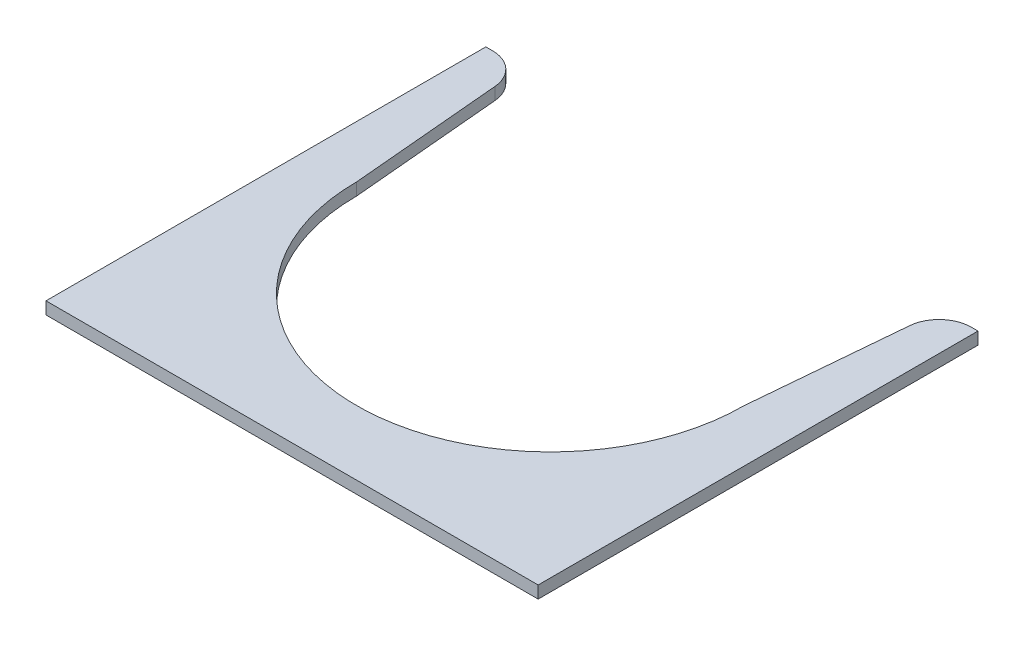
SolidWorks part; units mm, degrees
ref_plane "Front Plane" through (0, 0, 0) normal (0, 0, 1) x (1, 0, 0)
ref_plane "Top Plane" through (0, 0, 0) normal (0, 1, 0) x (1, 0, 0)
ref_plane "Right Plane" through (0, 0, 0) normal (1, 0, 0) x (0, 0, -1)
sketch "Sketch1" plane through (0, 0, 0) normal (0, 1, 0) x (1, 0, 0)
  line L1 (0, 0) -> (193.548, 0)
  line L2 (0, 0) -> (0, 172.974)
  line L3 (0, 172.974) -> (193.548, 172.974)
  line L4 (193.548, 0) -> (193.548, 172.974)
  dimension "D1" = 193.548
  dimension "D2" = 172.974
extrude "Base" add sketch "Sketch1" along normal blind 4.826
sketch "Sketch2" plane through (0, 4.826, 0) normal (0, 1, 0) x (1, 0, 0)
  line L0 (0, 172.974) -> (0, 0) construction
  line L1 (0, 0) -> (193.548, 0) construction
  line L2 (20.574, 101.6) -> (14.224, 172.974)
  line L3 (193.548, 172.974) -> (0, 172.974) construction
  line L4 (14.224, 172.974) -> (179.324, 172.974)
  line L5 (179.324, 172.974) -> (172.974, 101.6)
  line L6 (14.224, 172.974) -> (0, 172.974) construction
  line L7 (179.324, 172.974) -> (193.548, 172.974) construction
  line L8 (20.574, 101.6) -> (0, 101.6) construction
  line L9 (172.974, 101.6) -> (193.548, 101.6) construction
  line L10 (193.548, 0) -> (193.548, 172.974) construction
  line L11 (20.574, 101.6) -> (20.574, 172.974) construction
  line L12 (172.974, 101.6) -> (172.974, 172.974) construction
  line L13 (20.574, 101.6) -> (96.774, 101.6) construction
  line L14 (96.774, 101.6) -> (172.974, 101.6) construction
  arc A0 (20.574, 101.6) -> (172.974, 101.6) centre (96.774, 101.6) ccw
  dimension "D3" = 101.6
  dimension "D1" = 76.2
  dimension "D4" = 165.1
extrude "Center Cut" cut sketch "Sketch2" against normal through all
fillet "Leading Edge Fillet" radius 12.7 2 edges at (179.324, 2.413, -172.974) (14.224, 2.413, -172.974)
equation "\"material\"= \"gmaterial@Forklift_v2.assembly\""
equation "\"D1@Base\"=\"material\""
equation "\"D1@Sketch1\"=8-2*\"material\""
equation "\"D2@Sketch1\"=7-\"material\""
